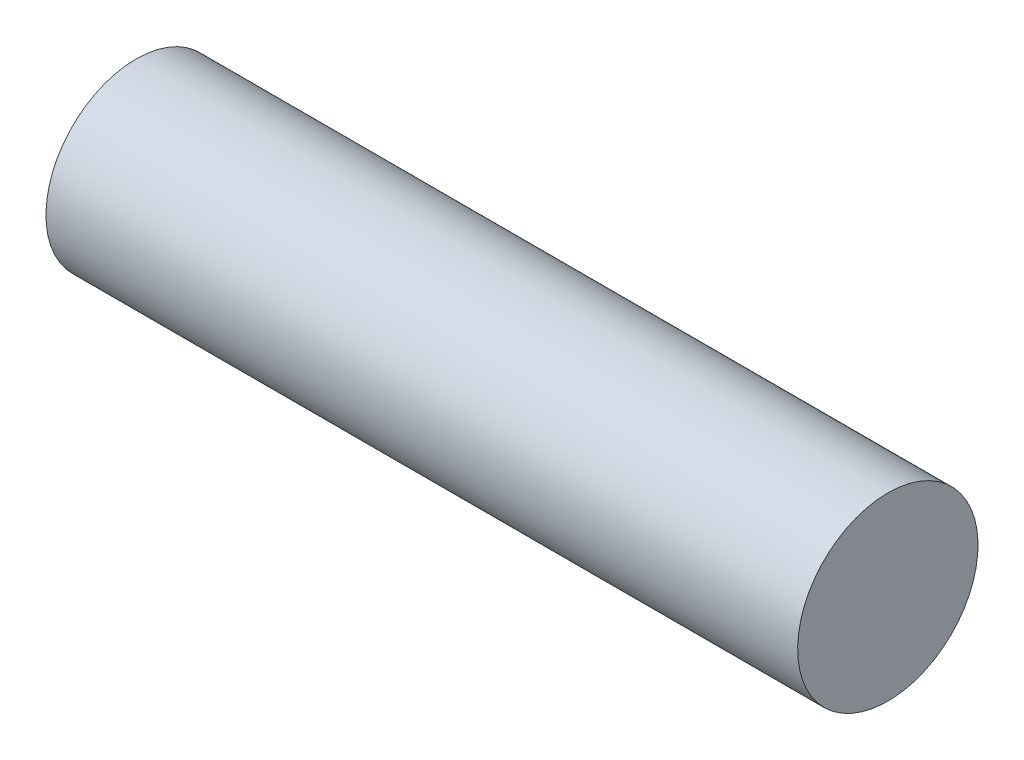
SolidWorks part; units mm, degrees
ref_plane "Front Plane" through (0, 0, 0) normal (0, 0, 1) x (1, 0, 0)
ref_plane "Top Plane" through (0, 0, 0) normal (0, 1, 0) x (1, 0, 0)
ref_plane "Right Plane" through (0, 0, 0) normal (1, 0, 0) x (0, 0, -1)
sketch "Sketch1" plane through (0, 0, 0) normal (0, 0, 1) x (1, 0, 0)
  line L0 (0, 0) -> (80, 0) construction
  line L1 (0, 0) -> (0, 6)
  line L2 (0, 6) -> (50, 6)
  line L3 (50, 6) -> (50, 0)
  line L4 (50, 0) -> (0, 0)
revolve "Revolve1" add sketch "Sketch1" angle 360 about L0
